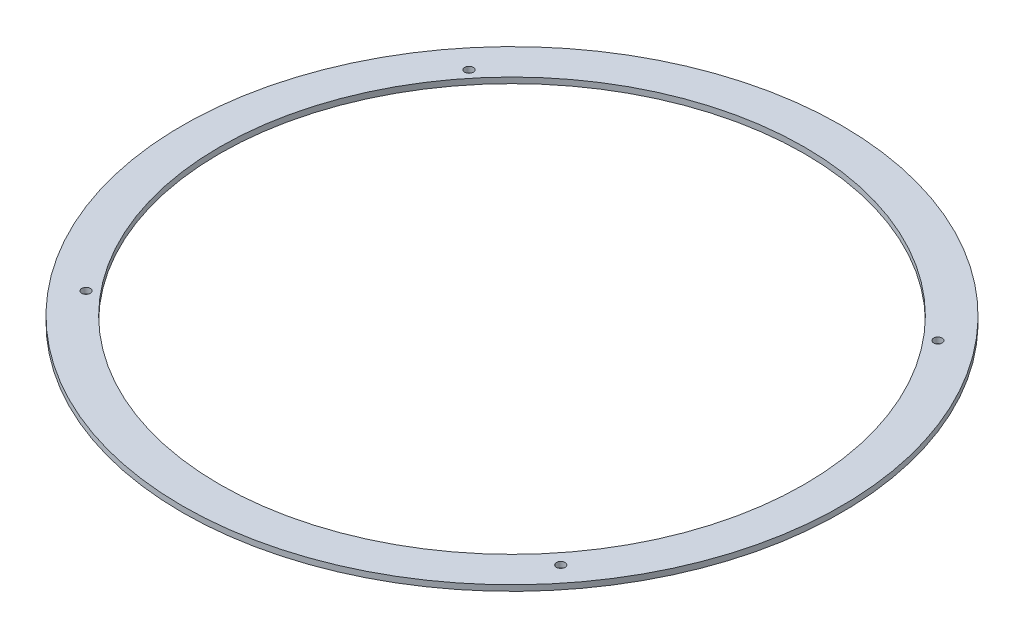
SolidWorks part; units mm, degrees
ref_plane "前视基准面" through (0, 0, 0) normal (0, 0, 1) x (1, 0, 0)
ref_plane "上视基准面" through (0, 0, 0) normal (0, 1, 0) x (1, 0, 0)
ref_plane "右视基准面" through (0, 0, 0) normal (1, 0, 0) x (0, 0, -1)
other "Configuration Table"
sketch "草图1" plane through (0, 0, 0) normal (0, 1, 0) x (1, 0, 0)
  circle A0 centre (0, 0) radius 102
  circle A1 centre (0, 0) radius 115
  circle A2 centre (-81.8198, 66.8198) radius 1.5
  circle A3 centre (-81.8198, -66.8198) radius 1.5
  circle A4 centre (83.8198, -66.8198) radius 1.5
  circle A5 centre (81.8198, 66.8198) radius 1.5
  point P5 (0, -102)
  point P32 (0.0184, -69.2688)
extrude "凸台-拉伸1" add sketch "草图1" along normal blind 2
